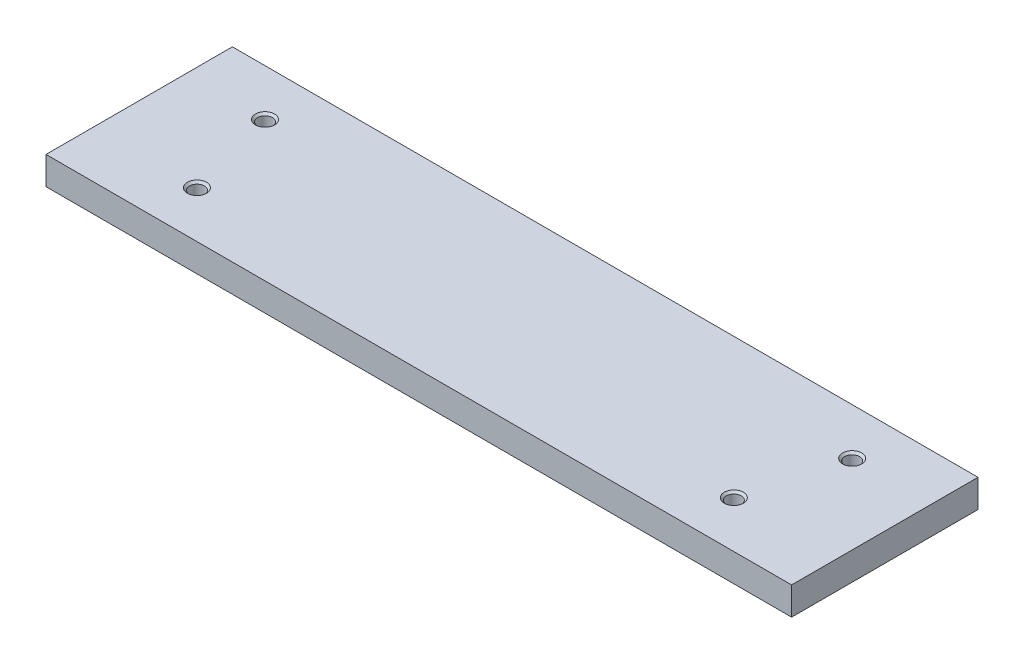
SolidWorks part; units mm, degrees
ref_plane "前视基准面" through (0, 0, 0) normal (0, 0, 1) x (1, 0, 0)
ref_plane "上视基准面" through (0, 0, 0) normal (0, 1, 0) x (1, 0, 0)
ref_plane "右视基准面" through (0, 0, 0) normal (1, 0, 0) x (0, 0, -1)
other "Configuration Table"
sketch "草图1" plane through (0, 0, 0) normal (0, 1, 0) x (1, 0, 0)
  line L0 (0, 0) -> (80, 0)
  line L2 (0, 0) -> (0, 20)
  line L3 (0, 20) -> (80, 20)
  line L4 (80, 0) -> (80, 20)
  dimension "D1" = 80
  dimension "D2" = 20
extrude "凸台-拉伸1" add sketch "草图1" along normal blind 3 contours L3 L4 L0 L2
sketch "草图2" plane through (0, 3, 0) normal (0, 1, 0) x (1, 0, 0)
  line L3 (0, 0) -> (80, 0) construction
  line L8 (0, 0) -> (0, 20) construction
  line L9 (0, 20) -> (80, 20) construction
  line L10 (80, 0) -> (80, 20) construction
  circle A0 centre (8.5, 15) radius 1
  circle A1 centre (71.5, 15) radius 1
  circle A2 centre (11.2, 5) radius 1
  circle A3 centre (68.8, 5) radius 1
  point P10 (8.5, 15)
  point P11 (71.5, 15)
  point P17 (11.2, 5)
  point P18 (68.8, 5)
  dimension "D2" = 5
  dimension "D4" = 8.5
  dimension "D1" = 2
  dimension "D10" = 2
  dimension "D11" = 2
  dimension "D3" = 2
  dimension "D5" = 5
  dimension "D6" = 8.5
  dimension "D7" = 5
  dimension "D8" = 11.2
  dimension "D9" = 5
  dimension "D12" = 11.2
sketch "草图6" plane through (0, 3, 0) normal (0, 1, 0) x (1, 0, 0)
  point P0 (8.5, 15)
  point P3 (11.2, 5)
  point P6 (71.5, 15)
  point P9 (68.8, 5)
hole_wizard "M2 螺纹孔1" positions "草图6" profile "草图7" tap size "M2" standard "GB" end condition through all
sketch "草图7" plane through (8.5, 3, -15) normal (1, 0, 0) x (0, 0, 1)
  line L0 (0, 0) -> (0, 3)
  line L1 (0, 3) -> (0.8, 3)
  line L2 (0.8, 3) -> (0.8, 0.225)
  line L3 (0.8, 0.225) -> (1.025, 0)
  line L5 (1.025, 0) -> (0, 0)
  line L6 (-0.8, 0.225) -> (-1.025, 0) construction
  line L11 (0, -6.35) -> (0, 107.95) construction
  dimension "通孔螺纹孔钻头直径" = 1.6
  dimension "通孔螺纹孔钻头深度" = 3
  dimension "近端锥形沉头孔直径" = 2.05
  dimension "近端锥形沉头孔角度" = 90
cosmetic thread "孔螺蚊线9" parameters "D2"=2
cosmetic thread "孔螺蚊线10" parameters "D2"=2
cosmetic thread "孔螺蚊线11" parameters "D2"=2
cosmetic thread "孔螺蚊线12" parameters "D2"=2
